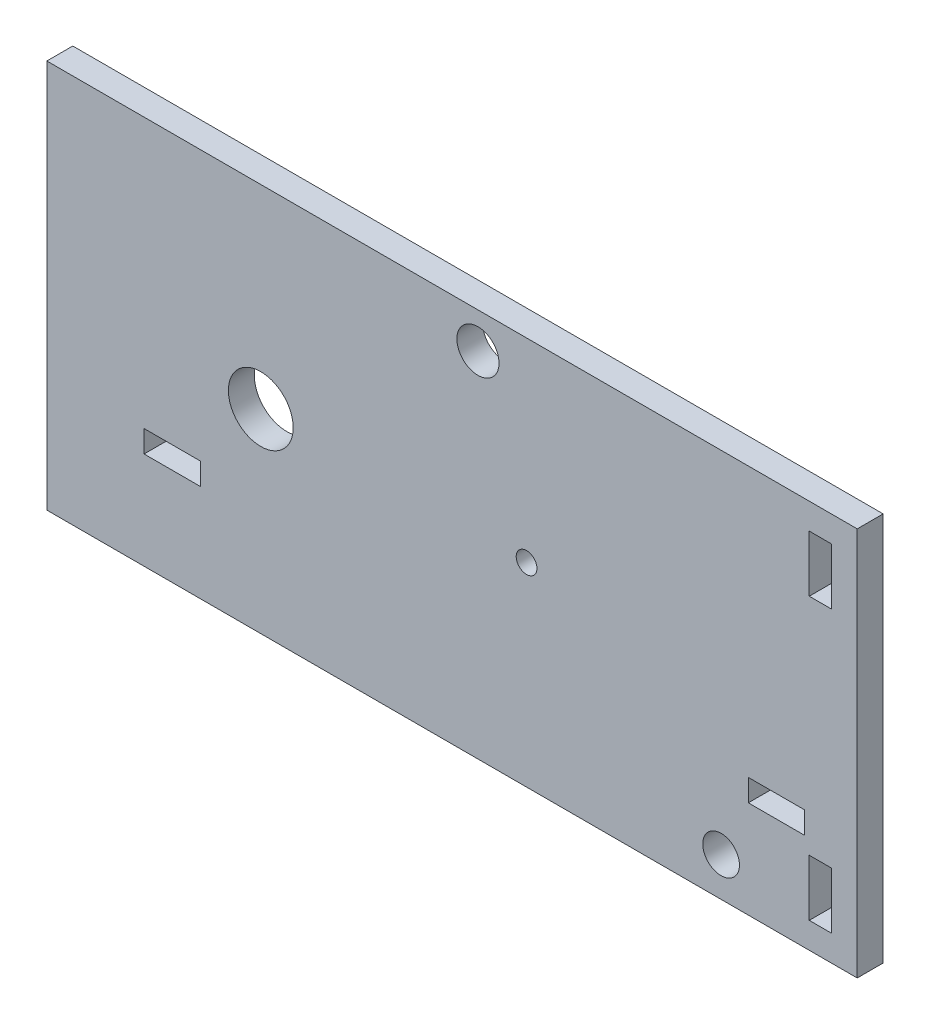
SolidWorks part; units mm, degrees
ref_plane "Front Plane" through (0, 0, 0) normal (0, 0, 1) x (1, 0, 0)
ref_plane "Top Plane" through (0, 0, 0) normal (0, 1, 0) x (1, 0, 0)
ref_plane "Right Plane" through (0, 0, 0) normal (1, 0, 0) x (0, 0, -1)
sketch "Sketch1" plane through (0, 0, 0) normal (0, 0, 1) x (1, 0, 0)
  line L1 (-79, -30) -> (42, -30)
  line L2 (-79, -30) -> (-79, 30)
  line L3 (-79, 30) -> (42, 30)
  line L4 (42, -30) -> (42, 30)
  line L5 (-64, -11.6) -> (-55.3, -11.6)
  line L6 (-64, -11.6) -> (-64, -15)
  line L7 (-64, -15) -> (-55.3, -15)
  line L8 (-55.3, -11.6) -> (-55.3, -15)
  line L9 (29.2, -11.6) -> (37.9, -11.6)
  line L10 (29.2, -11.6) -> (29.2, -15)
  line L11 (29.2, -15) -> (37.9, -15)
  line L12 (37.9, -11.6) -> (37.9, -15)
  circle A2 centre (-46, 0) radius 5
  circle A3 centre (-12.5, 24.5) radius 3.25
  circle A4 centre (25, -24) radius 2.83
  circle A5 centre (-5, 0) radius 1.6
  point P1 (0, 0)
  point P22 (-55.3, -13.3)
  point P24 (-79, 0)
  dimension "D3" = 15
  dimension "D4" = 121
  dimension "D5" = 33
  dimension "D6" = 8.7
  dimension "D7" = 33.5
  dimension "D10" = 6.5
  dimension "D12" = 104
  dimension "D13" = 6
  dimension "D14" = 5.66
  dimension "D15" = 54.5
  dimension "D18" = 41
  dimension "D19" = 24.5
  dimension "D20" = 10
  dimension "D21" = 10
  dimension "D2" = 60
  dimension "D8" = 3.4
  dimension "D9" = 15
  dimension "D11" = 15
  dimension "D16" = 84.5
extrude "Boss-Extrude1" add sketch "Sketch1" along normal blind 4
sketch "Sketch2" plane through (0, 0, 0) normal (0, 0, 1) x (1, 0, 0)
  line L0 (42, 30) -> (46, 30)
  line L1 (46, 30) -> (46, -30)
  line L2 (46, -30) -> (42, -30)
  line L13 (-79, -30) -> (42, -30) construction
  line L14 (42, -30) -> (42, 30)
  dimension "D1" = 4
extrude "Boss-Extrude2" add sketch "Sketch2" along normal blind 4
sketch "Sketch3" plane through (0, 0, 0) normal (0, 0, 1) x (1, 0, 0)
  line L0 (46, -30) -> (46, 30) construction
  line L1 (38.6, 26) -> (42, 26)
  line L2 (38.6, 26) -> (38.6, 17.3)
  line L3 (38.6, 17.3) -> (42, 17.3)
  line L4 (42, 26) -> (42, 17.3)
  line L5 (38.6, -17.3) -> (42, -17.3)
  line L6 (38.6, -17.3) -> (38.6, -26)
  line L7 (38.6, -26) -> (42, -26)
  line L8 (42, -17.3) -> (42, -26)
  line L9 (46, 30) -> (-79, 30) construction
  line L10 (-79, -30) -> (46, -30) construction
  dimension "D1" = 4
  dimension "D2" = 3.4
  dimension "D3" = 8.7
  dimension "D4" = 4
  dimension "D5" = 4
extrude "Cut-Extrude2" cut sketch "Sketch3" along normal through all both
equation "\"padding\"=4"
equation "\"hole_width\"=3.4"
equation "\"hole_height\"=8.7"
equation "\"D1@Sketch3\"=\"padding\""
equation "\"D2@Sketch3\"=\"hole_width\""
equation "\"D3@Sketch3\"=\"hole_height\""
equation "\"D4@Sketch3\"=\"padding\""
equation "\"D5@Sketch3\"=\"padding\""
